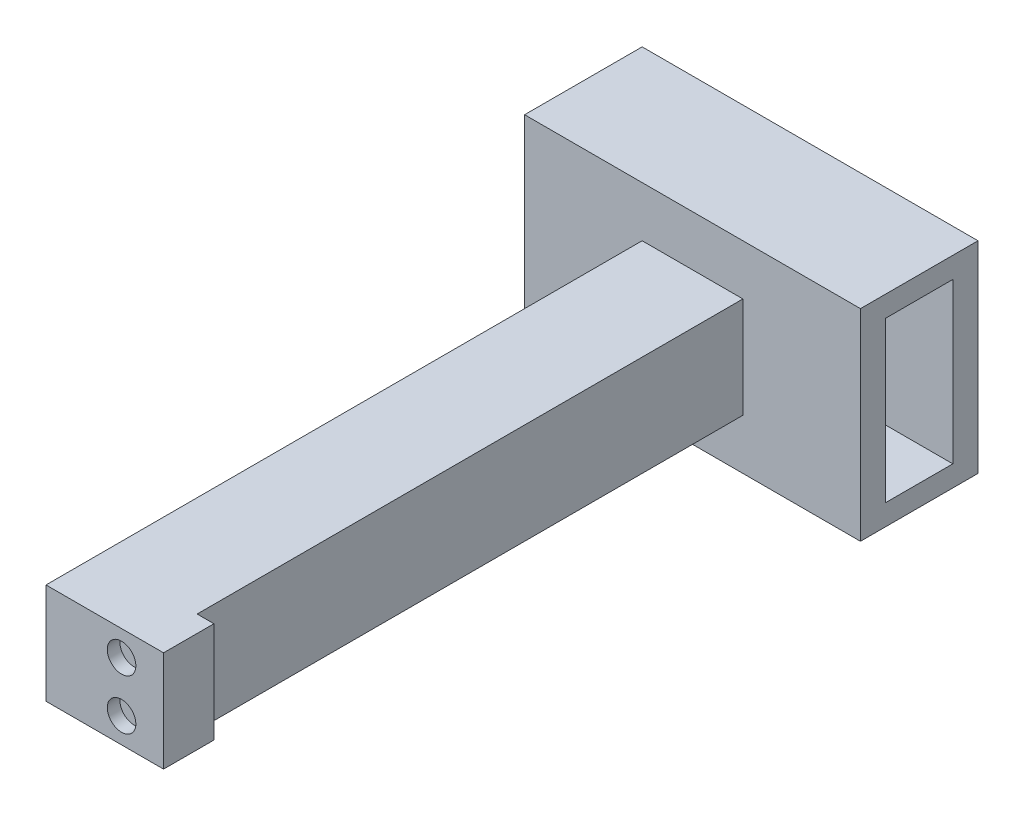
SolidWorks part; units mm, degrees
material "7075-T6 (SN)"
ref_plane "Front Plane" through (0, 0, 0) normal (0, 0, 1) x (1, 0, 0)
ref_plane "Top Plane" through (0, 0, 0) normal (0, 1, 0) x (1, 0, 0)
ref_plane "Right Plane" through (0, 0, 0) normal (1, 0, 0) x (0, 0, -1)
sketch "Sketch1" plane through (0, 0, 0) normal (0, 0, 1) x (1, 0, 0)
  line L1 (-44, -26) -> (-30, -26)
  line L2 (-44, -26) -> (-44, -14)
  line L3 (-44, -14) -> (-30, -14)
  line L4 (-30, -26) -> (-30, -14)
  circle A0 centre (-35, -23) radius 1.7
  circle A1 centre (-35, -17) radius 1.7
extrude "Outboard_Foot" add sketch "Sketch1" along normal blind 6 from offset 6
sketch "Sketch2" plane through (0, 0, 0) normal (0, 0, 1) x (1, 0, 0)
  line L1 (-44, -26) -> (-32, -26)
  line L2 (-44, -26) -> (-44, -14)
  line L3 (-44, -14) -> (-32, -14)
  line L4 (-32, -26) -> (-32, -14)
extrude "Drop_Web" add sketch "Sketch2" along normal blind 69.5 from offset 71
sketch "Sketch3" plane through (0, 0, 0) normal (0, 0, 1) x (1, 0, 0)
  line L1 (-58, -32) -> (-18, -32)
  line L2 (-58, -32) -> (-58, -8)
  line L3 (-58, -8) -> (-18, -8)
  line L4 (-18, -32) -> (-18, -8)
extrude "Cross_Slot_Block" add sketch "Sketch3" along normal blind 14 from offset 85
sketch "Sketch4" plane through (0, 0, 0) normal (1, 0, 0) x (0, 0, -1)
  line L0 (82, -29.51) -> (82, -10.49)
  line L1 (82, -10.49) -> (74, -10.49)
  line L2 (74, -10.49) -> (74, -29.51)
  line L3 (74, -29.51) -> (82, -29.51)
extrude "X_Floating_Y_Driven_Slot" cut sketch "Sketch4" against normal through all and the other way through all
